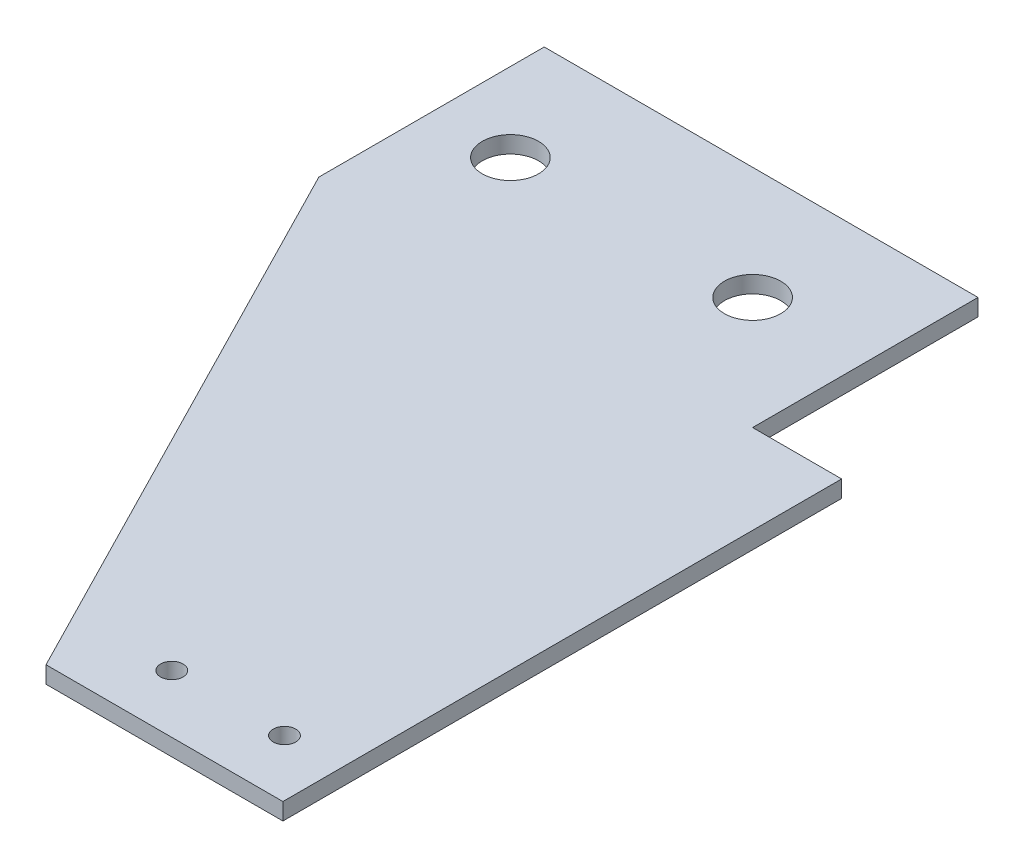
SolidWorks part; units mm, degrees
ref_plane "Front Plane" through (0, 0, 0) normal (0, 0, 1) x (1, 0, 0)
ref_plane "Top Plane" through (0, 0, 0) normal (0, 1, 0) x (1, 0, 0)
ref_plane "Right Plane" through (0, 0, 0) normal (1, 0, 0) x (0, 0, -1)
sketch "Sketch1" plane through (0, 0, 0) normal (0, 1, 0) x (1, 0, 0)
  line L0 (-46.3931, 71.58) -> (-7.9, 71.58)
  line L1 (-46.3931, 71.58) -> (-46.3931, 51.58)
  line L3 (0, 51.58) -> (0, 2)
  line L4 (-20, 12.7) -> (-20, 2)
  line L5 (0, 12.7) -> (-20, 12.7)
  line L6 (-46.3931, 51.58) -> (0, 51.58)
  line L7 (-7.9, 71.58) -> (-7.9, 51.58)
  line L8 (-21.0234, 2) -> (-46.3931, 51.58)
  line L10 (-46.3931, 61.58) -> (-7.9, 61.58)
  line L11 (-21.0234, 2) -> (0, 2)
  circle A0 centre (-15, 7.14) radius 1
  circle A1 centre (-5, 7.14) radius 1
  circle A2 centre (-39.3931, 61.58) radius 2.5
  circle A4 centre (-17.9, 61.58) radius 2.5
  dimension "D2" = 5
  dimension "D10" = 17.9
  dimension "D13" = 39.3931
  dimension "D1" = 2
  dimension "D3" = 5
  dimension "D4" = 7.9
  dimension "D5" = 15
  dimension "D6" = 46.3931
  dimension "D7" = 7.14
  dimension "D8" = 12.7
  dimension "D9" = 51.58
  dimension "D11" = 20
  dimension "D12" = 21.0234
  dimension "D14" = 2
  dimension "D15" = 61.58
extrude "Boss-Extrude1" add sketch "Sketch1" along normal blind 1.5
